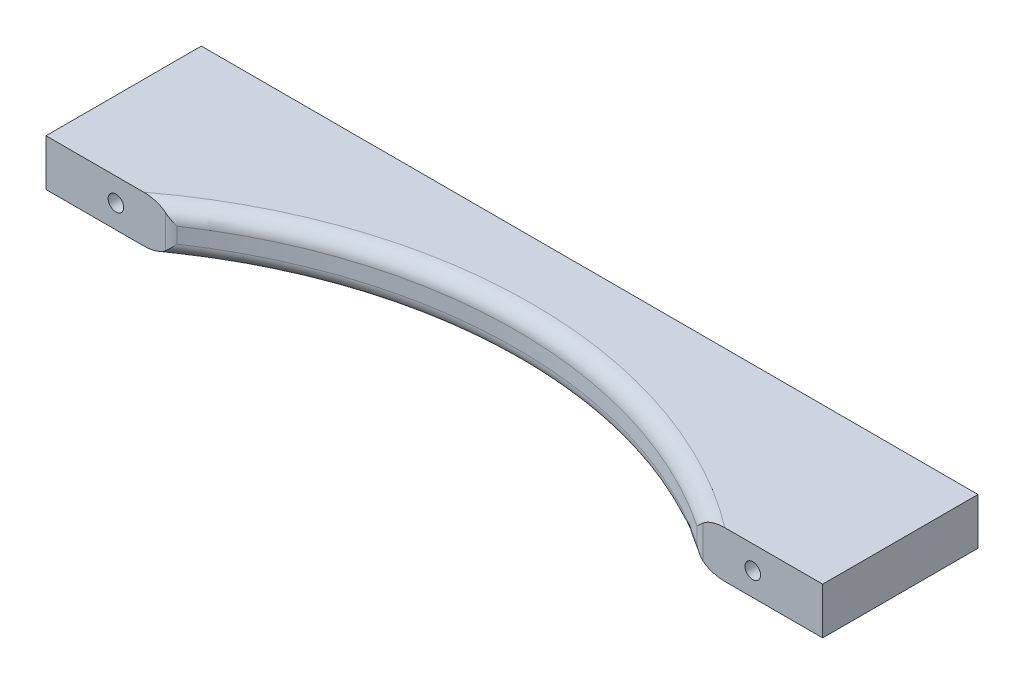
SolidWorks part; units mm, degrees
ref_plane "Front Plane" through (0, 0, 0) normal (0, 0, 1) x (1, 0, 0)
ref_plane "Top Plane" through (0, 0, 0) normal (0, 1, 0) x (1, 0, 0)
ref_plane "Right Plane" through (0, 0, 0) normal (1, 0, 0) x (0, 0, -1)
sketch "Sketch1" plane through (0, 0, 0) normal (0, 0, 1) x (1, 0, 0)
  line L0 (80, -31.25) -> (80, -46.25) construction
  line L1 (80, -46.25) -> (102.5, -46.25)
  line L2 (102.5, -71.75) -> (102.5, -5.75) construction
  line L3 (102.5, -46.25) -> (102.5, -31.25)
  line L4 (102.5, -31.25) -> (80, -31.25)
  line L5 (80, -31.25) -> (-147.5, -31.25)
  line L6 (-147.5, -5.75) -> (-147.5, -71.75) construction
  line L7 (-147.5, -31.25) -> (-147.5, -46.25)
  line L8 (-147.5, -46.25) -> (80, -46.25)
  circle A0 centre (-125, -38.75) radius 2.5 construction
  circle A1 centre (80, -38.75) radius 2.5 construction
  circle A2 centre (-125, -38.75) radius 2.5
  circle A3 centre (80, -38.75) radius 2.5
  point P9 (80, -38.75)
  dimension "D1" = 15
extrude "Boss-Extrude1" add sketch "Sketch1" along normal blind 50
sketch "Sketch2" plane through (0, -46.25, 0) normal (0, -1, 0) x (1, 0, 0)
  line L0 (102.5, 50) -> (62.5, 50) construction
  line L1 (-147.5, 50) -> (102.5, 50) construction
  line L2 (-147.5, 50) -> (-107.5, 50) construction
  line L3 (-107.5, 50) -> (62.5, 50)
  arc A0 (-107.5, 50) -> (62.5, 50) centre (-22.5, 173.5921) ccw
  point P8 (-22.5, 23.5921)
  dimension "D1" = 40
  dimension "D2" = 40
extrude "Cut-Extrude1" cut sketch "Sketch2" against normal up to surface (15 mm away) up to face at (-22.5, -31.25, 25)
fillet "Fillet1" radius 5 4 edges at (-22.5, -31.25, 23.5921) (-22.5, -46.25, 23.5921) (-107.5, -38.75, 50) (62.5, -38.75, 50)
